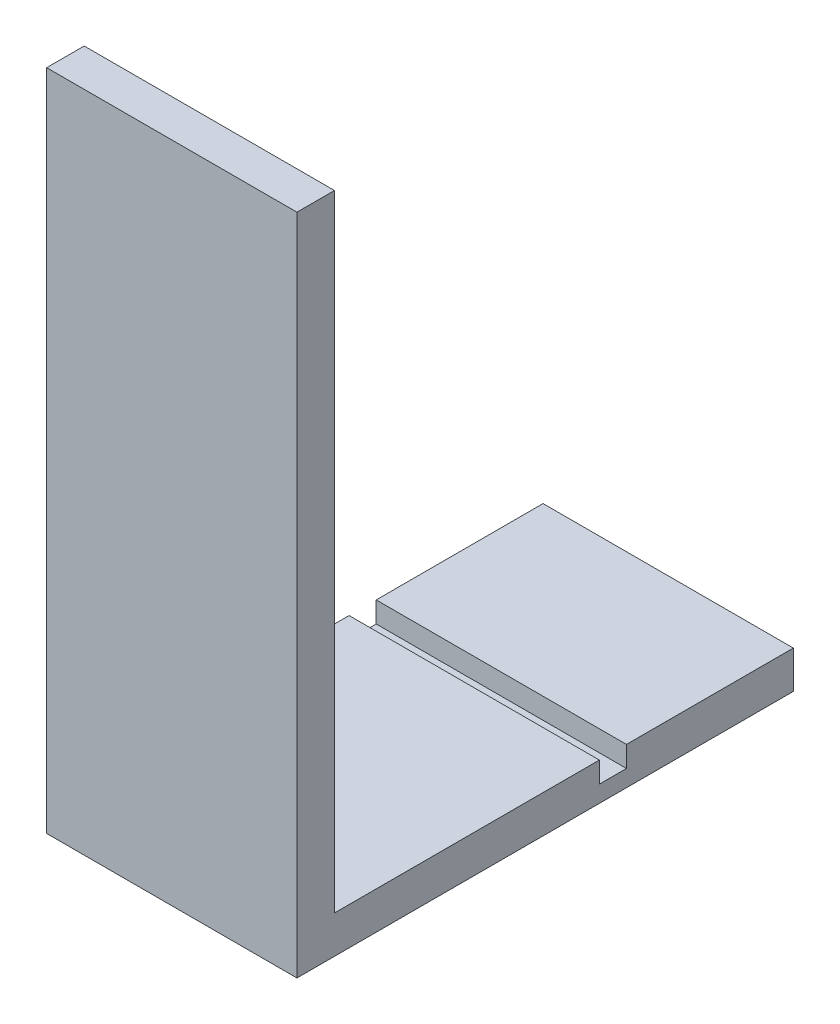
SolidWorks part; units mm, degrees
ref_plane "前基準面" through (0, 0, 0) normal (0, 0, 1) x (1, 0, 0)
ref_plane "上基準面" through (0, 0, 0) normal (0, 1, 0) x (1, 0, 0)
ref_plane "右基準面" through (0, 0, 0) normal (1, 0, 0) x (0, 0, -1)
sketch "草圖1" plane through (0, 0, 0) normal (1, 0, 0) x (0, 0, -1)
  line L0 (-179.6667, 241.3333) -> (-179.6667, -76.6667)
  line L1 (-179.6667, -76.6667) -> (58.3333, -76.6667)
  line L2 (58.3333, -76.6667) -> (58.3333, -58.6667)
  line L3 (58.3333, -58.6667) -> (-161.6667, -58.6667)
  line L4 (-161.6667, -58.6667) -> (-161.6667, 241.3333)
  line L5 (-161.6667, 241.3333) -> (-179.6667, 241.3333)
  dimension "D1" = 318
  dimension "D2" = 238
  dimension "D3" = 18
  dimension "D4" = 18
extrude "填料-伸長1" add sketch "草圖1" along normal blind 120
sketch "草圖2" plane through (120, 0, 0) normal (1, 0, 0) x (0, 0, -1)
  line L0 (-34.6667, -58.6667) -> (-34.6667, -68.6667)
  line L1 (-34.6667, -68.6667) -> (-21.6667, -68.6667)
  line L2 (-21.6667, -68.6667) -> (-21.6667, -58.6667)
  line L3 (-21.6667, -58.6667) -> (-34.6667, -58.6667)
  line L4 (58.3333, -58.6667) -> (-161.6667, -58.6667) construction
  line L5 (58.3333, -76.6667) -> (58.3333, -58.6667) construction
  dimension "D1" = 13
  dimension "D2" = 10
  dimension "D3" = 0
  dimension "D4" = 80
extrude "除料-伸長1" cut sketch "草圖2" against normal through all
